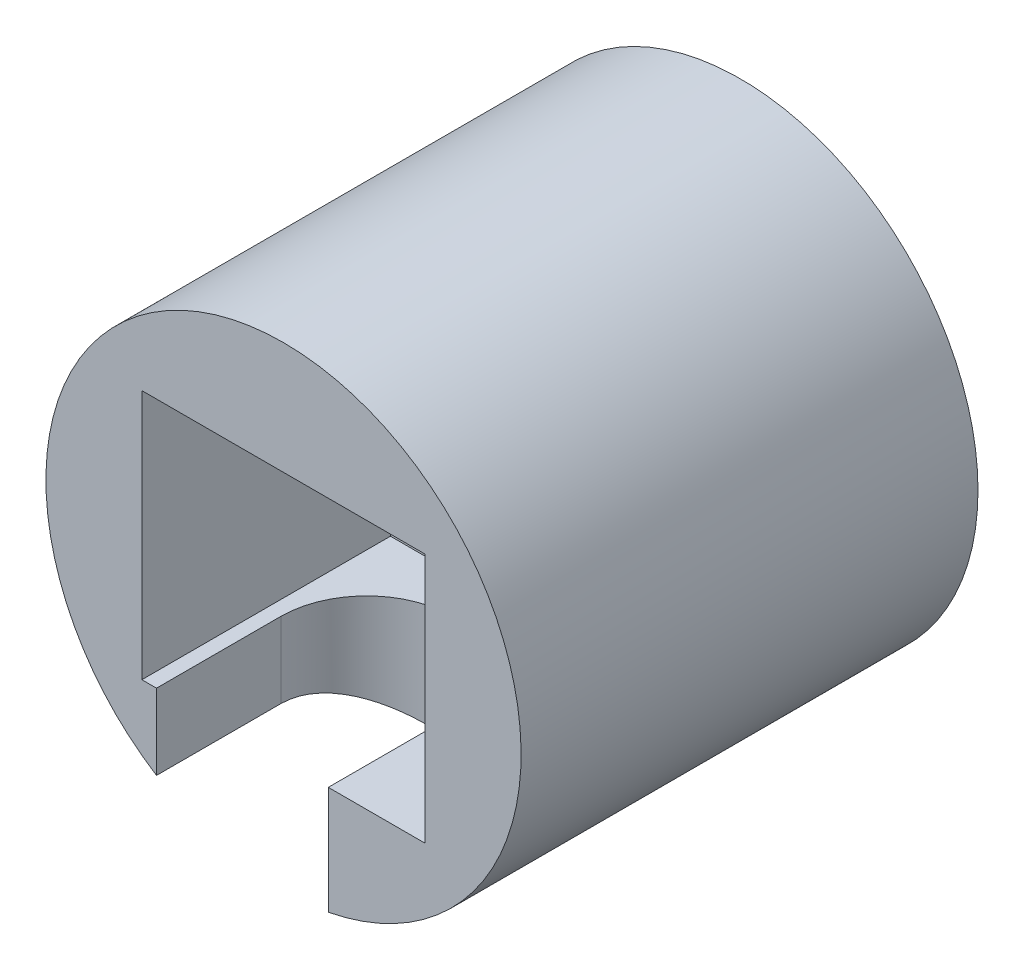
SolidWorks part; units mm, degrees
ref_plane "Front Plane" through (0, 0, 0) normal (0, 0, 1) x (1, 0, 0)
ref_plane "Top Plane" through (0, 0, 0) normal (0, 1, 0) x (1, 0, 0)
ref_plane "Right Plane" through (0, 0, 0) normal (1, 0, 0) x (0, 0, -1)
sketch "Sketch1" plane through (0, 0, 0) normal (0, 0, 1) x (1, 0, 0)
  circle A1 centre (0, 0) radius 3
  circle A2 centre (0, 0) radius 13
extrude "Boss-Extrude1" add sketch "Sketch1" along normal blind 25
sketch "Sketch2" plane through (0, 0, 0) normal (0, 1, 0) x (1, 0, 0)
  line L8 (-7.75, -25) -> (-7.75, -11.4)
  line L9 (-7.75, -11.4) -> (7.75, -11.4)
  line L10 (-7.75, -25) -> (7.75, -25)
  line L11 (7.75, -25) -> (7.75, -11.4)
extrude "Cut-Extrude1" cut sketch "Sketch2" against normal mid plane 13.7
sketch "Sketch3" plane through (0, 0, 0) normal (0, 1, 0) x (1, 0, 0)
  line L6 (-6.95, -18.2) -> (-6.95, -25)
  line L7 (-6.95, -25) -> (2.45, -25)
  line L8 (2.45, -18.2) -> (2.45, -25)
  arc A1 (2.45, -18.2) -> (-6.95, -18.2) centre (-2.25, -18.2) ccw
extrude "Cut-Extrude2" cut sketch "Sketch3" against normal up to surface (12.767 mm away)
